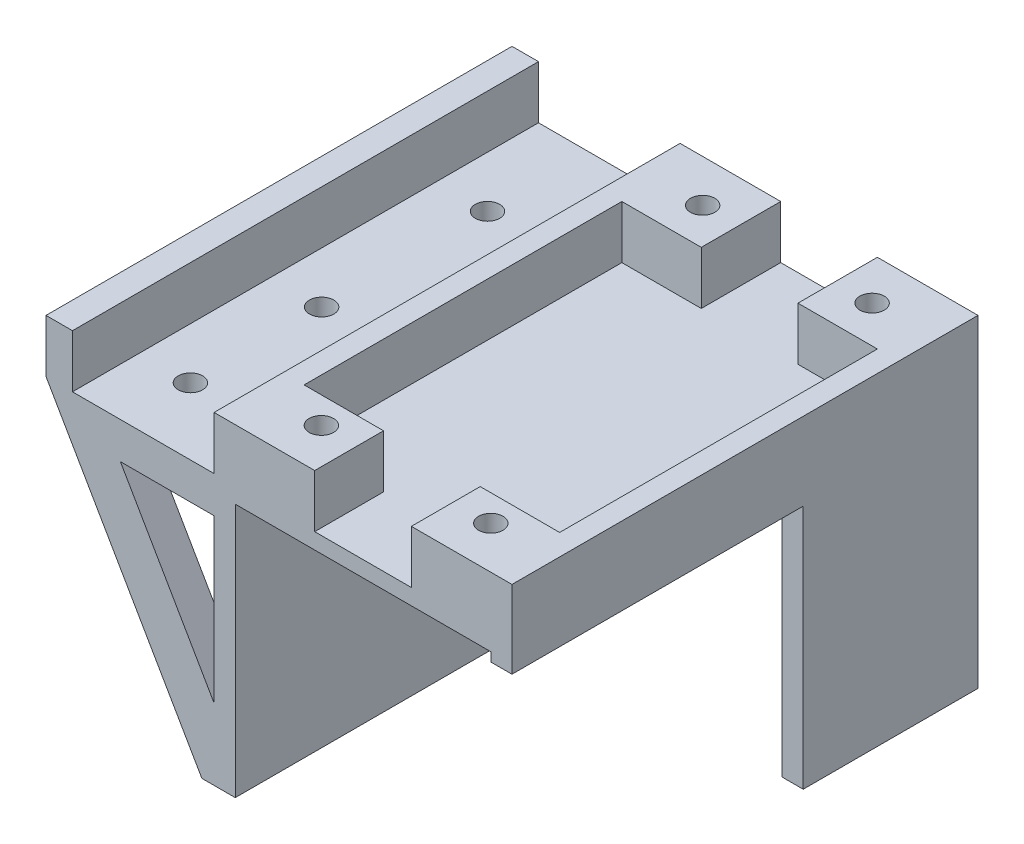
SolidWorks part; units mm, degrees
ref_plane "Front" through (0, 0, 0) normal (0, 0, 1) x (1, 0, 0)
ref_plane "Top" through (0, 0, 0) normal (0, 1, 0) x (1, 0, 0)
ref_plane "Right" through (0, 0, 0) normal (1, 0, 0) x (0, 0, -1)
sketch "Sketch1" plane through (0, 0, 0) normal (0, 0, 1) x (1, 0, 0)
  line L0 (0, 0) -> (0, 70)
  line L1 (0, 70) -> (56.254, 70)
  line L2 (56.254, 70) -> (56.254, 0)
  line L3 (56.254, 0) -> (52.254, 0)
  line L4 (52.254, 0) -> (52.254, 65)
  line L5 (52.254, 65) -> (4, 65)
  line L6 (4, 65) -> (4, 0)
  line L7 (4, 0) -> (0, 0)
  line L9 (4, 55) -> (52.254, 55)
  line L10 (4, 55) -> (4, 52)
  line L11 (4, 52) -> (52.254, 52)
  line L12 (52.254, 55) -> (52.254, 52)
  dimension "D1" = 48.254
  dimension "D2" = 4
  dimension "D3" = 4
  dimension "D4" = 5
  dimension "D5" = 70
  dimension "D6" = 3
  dimension "D7" = 10
extrude "Boss-Extrude1" add sketch "Sketch1" along normal blind 70 contours L7 L6 L5 L4 L3 L2 L1 L0 | L9 L12 L11 L10
sketch "Sketch3" plane through (0, 0, 70) normal (0, 0, 1) x (1, 0, 0)
  line L0 (0, 70) -> (-40.3946, 70)
  line L1 (-40.3946, 70) -> (0, 0.0344)
  line L2 (0, 0) -> (0, 70) construction
  line L3 (0, 0.0344) -> (0, 70)
  line L4 (0, 70) -> (0, 62.5)
  line L5 (0, 62.5) -> (-26, 62.5)
  line L6 (-26, 62.5) -> (0, 17.4667)
  line L7 (0, 17.4667) -> (0, 0.0344)
  line M11 (0, 70) -> (0, 0)
  dimension "D1" = 60
  dimension "D2" = 180
  dimension "D3" = 7.5
  dimension "D4" = 26
extrude "Boss-Extrude3" add sketch "Sketch3" against normal blind 8 contours L6 L5 L0 L1 M11
sketch "Sketch4" plane through (0, 0, 0) normal (0, 0, -1) x (-1, 0, 0)
  line L0 (0, 70) -> (40.3946, 70)
  line L1 (40.3946, 70) -> (0, 0)
  line L2 (0, 0) -> (0, 17.4667)
  line L3 (0, 17.4667) -> (26, 62.5)
  line L4 (26, 62.5) -> (0, 62.5)
  line L5 (0, 62.5) -> (0, 70)
extrude "Boss-Extrude4" add sketch "Sketch4" against normal blind 8
ref_plane "Plane1" through (0, 0, 39) normal (0, 0, -1) x (-1, 0, 0)
sketch "Sketch5" plane through (0, 0, 39) normal (0, 0, -1) x (-1, 0, 0)
  line L0 (0, 62.5) -> (0, 70)
  line L1 (0, 70) -> (40.3946, 70)
  line L2 (40.3946, 70) -> (0, 0)
  line L3 (0, 0) -> (0, 17.4667)
  line L4 (0, 17.4667) -> (26, 62.5)
  line L5 (26, 62.5) -> (0, 62.5)
extrude "Boss-Extrude5" add sketch "Sketch5" along normal blind 8
sketch "Sketch6" plane through (0, 0, 0) normal (0, 0, -1) x (-1, 0, 0)
  line L5 (0, 62.5) -> (36.0666, 62.5)
  line L6 (0, 0) -> (40.3946, 70) construction
  line L7 (36.0666, 62.5) -> (40.3946, 70)
  line L8 (40.3946, 70) -> (0, 70)
  line L9 (40.3946, 70) -> (-56.254, 70) construction
  line L10 (0, 70) -> (0, 62.5)
  line L11 (-4, 0) -> (0, 0)
  line L12 (0, 0) -> (7.5019, 13)
  line L13 (7.5019, 13) -> (-4, 13)
  line L14 (-4, 52) -> (-4, 0) construction
  line L15 (-4, 13) -> (-4, 0)
  dimension "D1" = 13
extrude "Boss-Extrude6" add sketch "Sketch6" against normal blind 70
sketch "Sketch7" plane through (0, 0, 70) normal (0, 0, 1) x (1, 0, 0)
  line L0 (0, 17.4667) -> (0, 62.5) construction
  line L1 (-40.3946, 70) -> (0, 70)
  line L2 (-40.3946, 70) -> (-40.3946, 53)
  line L3 (-40.3946, 53) -> (0, 53)
  line L4 (0, 70) -> (0, 53)
  dimension "D1" = 17
extrude "Cut-Extrude3" cut sketch "Sketch7" against normal blind 70
sketch "Sketch8" plane through (0, 0, 0) normal (0, 0, -1) x (-1, 0, 0)
  line L1 (-4, 55) -> (-4, 52)
  line L2 (-4, 52) -> (-52.254, 52) construction
  line L3 (-4, 52) -> (30.0074, 52)
  line L4 (0, 0) -> (30.5845, 53) construction
  line L6 (30.0074, 52) -> (31.7386, 55)
  line L7 (31.7386, 55) -> (-4, 55)
  dimension "D1" = 180
extrude "Boss-Extrude7" add sketch "Sketch8" against normal blind 70
sketch "Sketch11" plane through (0, 0, 70) normal (0, 0, 1) x (1, 0, 0)
  line L0 (-31.7386, 55) -> (0, 0)
  line L3 (-31.7386, 55) -> (0, 55) construction
  line L4 (-27.289, 55) -> (-31.7386, 55)
  line L5 (-27.289, 55) -> (-3.0537, 13)
  line L6 (-3.0537, 13) -> (0, 0)
extrude "Boss-Extrude10" add sketch "Sketch11" against normal blind 8
sketch "Sketch12" plane through (0, 0, 70) normal (0, 0, 1) x (1, 0, 0)
  line L0 (-31.7386, 55) -> (-27.7598, 48.1051)
  line L1 (0, 0) -> (-31.7386, 55) construction
  line L2 (-27.7598, 48.1051) -> (0, 48.1051)
  line L3 (0, 17.4667) -> (0, 52) construction
  line L4 (0, 48.1051) -> (0, 55)
  line L5 (0, 55) -> (-31.7386, 55)
extrude "Boss-Extrude11" add sketch "Sketch12" against normal blind 70
sketch "Sketch13" plane through (0, 0, 0) normal (0, -1, 0) x (1, 0, 0)
  line L1 (67.4394, -10.6205) -> (-15.562, -10.6205)
  line L2 (67.4394, -10.6205) -> (67.4394, 77.2481)
  line L3 (67.4394, 77.2481) -> (-15.562, 77.2481)
  line L4 (-15.562, -10.6205) -> (-15.562, 77.2481)
extrude "Cut-Extrude4" cut sketch "Sketch13" against normal blind 4
sketch "Sketch14" plane through (0, 0, 70) normal (0, 0, 1) x (1, 0, 0)
  line L0 (-2.3083, 4) -> (-31.7386, 55)
  line L1 (-31.7386, 55) -> (0, 55)
  line L2 (0, 55) -> (0, 70)
  line L3 (0, 70) -> (56.254, 70)
  line L4 (56.254, 70) -> (56.254, 4)
  line L5 (56.254, 4) -> (52.254, 4)
  line L6 (52.254, 4) -> (52.254, 52)
  line L7 (52.254, 52) -> (4, 52)
  line L8 (4, 52) -> (4, 4)
  line L9 (4, 4) -> (-2.3083, 4)
  line L14 (-17.6891, 48.1051) -> (0, 48.1051)
  line L15 (52.254, 55) -> (4, 55)
  line L16 (52.254, 55) -> (52.254, 65)
  line L17 (52.254, 65) -> (4, 65)
  line L18 (4, 55) -> (4, 65)
  line L19 (-17.6891, 48.1051) -> (0, 48.1051) construction
  line L20 (0, 48.1051) -> (0, 17.4667)
  line L21 (0, 17.4667) -> (-17.6891, 48.1051)
extrude "Boss-Extrude12" add sketch "Sketch14" along normal blind 20
sketch "Sketch15" plane through (0, 0, 90) normal (0, 0, 1) x (1, 0, 0)
  line L0 (56.254, 4) -> (56.254, 70) construction
  line L1 (56.254, 65) -> (37.264, 65)
  line L2 (56.254, 65) -> (56.254, 55)
  line L3 (56.254, 55) -> (37.264, 55)
  line L4 (37.264, 65) -> (37.264, 55)
  line L5 (4, 55) -> (52.254, 55) construction
  dimension "D1" = 18.99
sketch "Sketch16" plane through (0, 0, 90) normal (0, 0, 1) x (1, 0, 0)
  line L1 (0, 70) -> (56.254, 70)
  line L2 (0, 70) -> (0, 65)
  line L3 (0, 65) -> (56.254, 65)
  line L4 (56.254, 70) -> (56.254, 65)
extrude "Cut-Extrude5" cut sketch "Sketch16" against normal blind 100
sketch "Sketch17" plane through (0, 65, 0) normal (0, 1, 0) x (1, 0, 0)
  line L1 (52.254, 0) -> (37.254, 0)
  line L2 (52.254, 0) -> (52.254, -15)
  line L3 (52.254, -15) -> (37.254, -15)
  line L4 (37.254, 0) -> (37.254, -15)
  line L5 (52.254, -90) -> (37.254, -90)
  line L6 (52.254, -90) -> (52.254, -75)
  line L7 (52.254, -75) -> (37.254, -75)
  line L8 (37.254, -90) -> (37.254, -75)
  dimension "D1" = 15
  dimension "D2" = 15
  dimension "D3" = 15
  dimension "D4" = 15
extrude "Boss-Extrude14" add sketch "Sketch17" against normal blind 13
sketch "Sketch21" plane through (0, 52, 0) normal (0, -1, 0) x (-1, 0, 0)
  circle A0 centre (-44.254, -80) radius 2.3
  circle A1 centre (-44.254, -8) radius 2.3
sketch "Sketch22" plane through (0, 52, 0) normal (0, -1, 0) x (1, 0, 0)
  line L1 (48.0965, 6.0036) -> (47.9041, 10.3295)
  line L2 (47.9041, 10.3295) -> (44.0617, 12.3259)
  line L3 (44.0617, 12.3259) -> (40.4115, 9.9964)
  line L4 (40.4115, 9.9964) -> (40.6039, 5.6705)
  line L5 (40.6039, 5.6705) -> (44.4463, 3.6741)
  line L6 (44.4463, 3.6741) -> (48.0965, 6.0036)
  line L7 (45.2007, 75.7746) -> (48.3866, 78.7072)
  line L8 (48.3866, 78.7072) -> (47.4399, 82.9325)
  line L9 (47.4399, 82.9325) -> (43.3073, 84.2254)
  line L10 (43.3073, 84.2254) -> (40.1214, 81.2928)
  line L11 (40.1214, 81.2928) -> (41.0681, 77.0675)
  line L12 (41.0681, 77.0675) -> (45.2007, 75.7746)
  circle A0 centre (44.254, 8) radius 3.75 construction
  circle A1 centre (44.254, 80) radius 3.75 construction
  point P10 (42.2366, 11.1611)
  dimension "D1" = 7.5
  dimension "D2" = 7.5
extrude "Cut-Extrude8" cut sketch "Sketch22" against normal blind 5
extrude "Cut-Extrude9" cut sketch "Sketch21" against normal blind 15
sketch "Sketch23" plane through (0, 0, 0) normal (-0.8661, -0.4998, 0) x (0, 0, 1)
  line L0 (90, 63.5007) -> (90, 4.6182) construction
  line L1 (70, 55.5401) -> (82, 55.5401)
  line L2 (70, 55.5401) -> (70, 15.0093)
  line L3 (70, 15.0093) -> (82, 15.0093)
  line L4 (82, 55.5401) -> (82, 15.0093)
  line L5 (62, 55.5401) -> (62, 15.0093) construction
  dimension "D1" = 8
  dimension "D2" = 8
extrude "Cut-Extrude10" cut sketch "Sketch23" against normal blind 9
sketch "Sketch25" plane through (0, 48.1051, 0) normal (0, -1, 0) x (-1, 0, 0)
  circle A0 centre (17.0755, -19.3006) radius 2.3
  circle A1 centre (17.0755, -50.6137) radius 2.3
extrude "Cut-Extrude11" cut sketch "Sketch25" against normal blind 20
sketch "Sketch26" plane through (0, 48.1051, 0) normal (0, -1, 0) x (1, 0, 0)
  circle A0 centre (-17.0755, 75.3913) radius 2.3
extrude "Cut-Extrude12" cut sketch "Sketch26" against normal blind 20
sketch "Sketch27" plane through (0, 0, 90) normal (0, 0, 1) x (1, 0, 0)
  line L0 (-23.3104, 48.1051) -> (-27.7598, 48.1051)
  line L1 (-31.7386, 55) -> (-2.3083, 4) construction
  line L2 (-27.7598, 48.1051) -> (-31.7386, 55)
  line L3 (-31.7386, 55) -> (-23.3104, 55)
  line L4 (0, 55) -> (-31.7386, 55) construction
  line L5 (-23.3104, 55) -> (-23.3104, 48.1051)
extrude "Boss-Extrude16" add sketch "Sketch27" against normal blind 20
sketch "Sketch28" plane through (0, 55, 0) normal (0, 1, 0) x (1, 0, 0)
  line L0 (4, -90) -> (37.254, -90) construction
  line L1 (4, 0) -> (19, 0)
  line L2 (4, 0) -> (4, -15)
  line L3 (4, -15) -> (19, -15)
  line L4 (19, 0) -> (19, -15)
  line L5 (4, -90) -> (19, -90)
  line L6 (4, -90) -> (4, -75)
  line L7 (4, -75) -> (19, -75)
  line L8 (19, -90) -> (19, -75)
  line L9 (4, 0) -> (4, -90) construction
  dimension "D1" = 15
  dimension "D2" = 15
  dimension "D3" = 15
  dimension "D4" = 15
extrude "Boss-Extrude17" add sketch "Sketch28" along normal blind 10
sketch "Sketch29" plane through (0, 52, 0) normal (0, -1, 0) x (-1, 0, 0)
  circle A0 centre (-12.254, -8) radius 2.3
  circle A1 centre (-12.254, -80) radius 2.3
extrude "Cut-Extrude13" cut sketch "Sketch29" against normal blind 20
sketch "Sketch30" plane through (0, 48.1051, 0) normal (0, -1, 0) x (1, 0, 0)
  line L1 (-27.7598, 70) -> (-17.3688, 70)
  line L2 (-27.7598, 70) -> (-27.7598, 82)
  line L3 (-27.7598, 82) -> (-17.3688, 82)
  line L4 (-17.3688, 70) -> (-17.3688, 82)
extrude "Boss-Extrude18" add sketch "Sketch30" against normal blind 5
sketch "Sketch31" plane through (0, 48.1051, 0) normal (0, -1, 0) x (1, 0, 0)
  circle A0 centre (-17.0755, 75.3913) radius 2.3
extrude "Cut-Extrude14" cut sketch "Sketch31" against normal blind 45
sketch "Sketch33" plane through (0, 55, 0) normal (0, 1, 0) x (1, 0, 0)
  circle A0 centre (27.6164, -46.5233) radius 1
  circle A1 centre (26.8974, -20.9206) radius 1
  circle A2 centre (28.9102, -66.6327) radius 1
  circle A3 centre (-20.9687, -5.2719) radius 1
  circle A4 centre (-23.4497, -23.5026) radius 1
  circle A5 centre (-17.8546, -42.0102) radius 1
  circle A6 centre (-22.4497, -64.7625) radius 1
  circle A7 centre (-17.8546, -85.6157) radius 1
ref_plane "Plane2" through (-31.7386, 55, 90) normal (0.4998, -0.8661, 0) x (-0.8661, -0.4998, 0)
sketch "Sketch36" plane through (0, 0, 90) normal (0, 0, 1) x (1, 0, 0)
  circle A0 centre (23.0361, 36.9328) radius 60.0365
extrude "Cut-Extrude15" cut sketch "Sketch36" against normal blind 2
sketch "Sketch37" plane through (0, 55, 0) normal (0, 1, 0) x (1, 0, 0)
  line L0 (-31.7386, -88) -> (0, -88) construction
  line L1 (-31.7386, 0) -> (-26.7386, 0)
  line L2 (-31.7386, 0) -> (-31.7386, -88)
  line L3 (-31.7386, -88) -> (-26.7386, -88)
  line L4 (-26.7386, 0) -> (-26.7386, -88)
  dimension "D1" = 5
extrude "Boss-Extrude19" add sketch "Sketch37" along normal blind 10
sketch "Sketch38" plane through (0, 52, 0) normal (0, -1, 0) x (1, 0, 0)
  line L1 (12.254, 75.6699) -> (16.004, 77.8349)
  line L2 (16.004, 77.8349) -> (16.004, 82.1651)
  line L3 (16.004, 82.1651) -> (12.254, 84.3301)
  line L4 (12.254, 84.3301) -> (8.504, 82.1651)
  line L5 (8.504, 82.1651) -> (8.504, 77.8349)
  line L6 (8.504, 77.8349) -> (12.254, 75.6699)
  line L7 (15.5673, 5.2122) -> (16.325, 9.4755)
  line L8 (16.325, 9.4755) -> (13.0117, 12.2633)
  line L9 (13.0117, 12.2633) -> (8.9407, 10.7878)
  line L10 (8.9407, 10.7878) -> (8.183, 6.5245)
  line L11 (8.183, 6.5245) -> (11.4963, 3.7367)
  line L12 (11.4963, 3.7367) -> (15.5673, 5.2122)
  circle A0 centre (12.254, 80) radius 3.75 construction
  circle A1 centre (12.254, 8) radius 3.75 construction
  dimension "D1" = 7.5
  dimension "D2" = 7.5
extrude "Cut-Extrude16" cut sketch "Sketch38" against normal blind 5
sketch "Sketch39" plane through (4, 0, 0) normal (1, 0, 0) x (0, 0, -1)
  circle A0 centre (-47.5147, 36.4853) radius 2.1
  circle A1 centre (-48, 20) radius 2.1
  circle A2 centre (-16.4853, 19.5147) radius 2.1
  circle A3 centre (-16.4853, 36.4853) radius 2.1
extrude "Cut-Extrude17" cut sketch "Sketch39" against normal blind 5
sketch "Sketch40" plane through (56.254, 0, 0) normal (1, 0, 0) x (0, 0, -1)
  line L0 (-88, 50.3083) -> (-33, 50.3083)
  line L1 (-88, 65) -> (-88, 4) construction
  line L2 (-88, 50.3083) -> (-88, 4)
  line L3 (-88, 4) -> (-33, 4)
  line L4 (-88, 4) -> (0, 4) construction
  line L5 (-33, 4) -> (-33, 50.3083)
  dimension "D1" = 55
extrude "Cut-Extrude18" cut sketch "Sketch40" against normal blind 5
